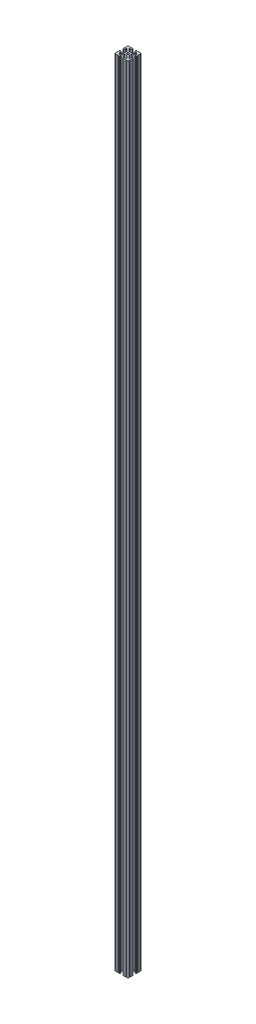
SolidWorks part; units mm, degrees
ref_plane "Piano frontale" through (0, 0, 0) normal (0, 0, 1) x (1, 0, 0)
ref_plane "Piano superiore" through (0, 0, 0) normal (0, 1, 0) x (1, 0, 0)
ref_plane "Piano destro" through (0, 0, 0) normal (1, 0, 0) x (0, 0, -1)
ref_plane "Piano1" through (0, 152.4, 0) normal (0, 1, 0) x (1, 0, 0)
sketch "Schizzo1" plane through (0, 152.4, 0) normal (0, 1, 0) x (1, 0, 0)
  line L0 (130, 32) -> (130, 33.688)
  line L1 (130, 34.312) -> (130, 37.688)
  line L2 (130, 38.312) -> (130, 40.4)
  line L3 (128.6, 41.8) -> (128.2, 41.8)
  line L4 (126.8, 40.4) -> (126.8, 37.3941)
  line L5 (125.4343, 36.8284) -> (120.9058, 41.357)
  line L6 (120.32, 42.7712) -> (120.32, 47.2288)
  line L7 (120.9058, 48.643) -> (125.4343, 53.1716)
  line L8 (126.8, 52.6059) -> (126.8, 49.6)
  line L9 (128.2, 48.2) -> (128.6, 48.2)
  line L10 (130, 49.6) -> (130, 51.688)
  line L11 (130, 52.312) -> (130, 55.688)
  line L12 (130, 56.312) -> (130, 58)
  line L13 (128, 60) -> (126.312, 60)
  line L14 (125.688, 60) -> (122.312, 60)
  line L15 (121.688, 60) -> (119.6, 60)
  line L16 (118.2, 58.6) -> (118.2, 58.2)
  line L17 (119.6, 56.8) -> (122.6059, 56.8)
  line L18 (123.1716, 55.4343) -> (118.643, 50.9058)
  line L19 (117.2288, 50.32) -> (112.7712, 50.32)
  line L20 (111.357, 50.9058) -> (106.8284, 55.4343)
  line L21 (107.3941, 56.8) -> (110.4, 56.8)
  line L22 (111.8, 58.2) -> (111.8, 58.6)
  line L23 (110.4, 60) -> (108.312, 60)
  line L24 (107.688, 60) -> (104.312, 60)
  line L25 (103.688, 60) -> (102, 60)
  line L26 (100, 58) -> (100, 56.312)
  line L27 (100, 55.688) -> (100, 52.312)
  line L28 (100, 51.688) -> (100, 49.6)
  line L29 (101.4, 48.2) -> (101.8, 48.2)
  line L30 (103.2, 49.6) -> (103.2, 52.6059)
  line L31 (104.5657, 53.1716) -> (109.0942, 48.643)
  line L32 (109.68, 47.2288) -> (109.68, 42.7712)
  line L33 (109.0942, 41.357) -> (104.5657, 36.8284)
  line L34 (103.2, 37.3941) -> (103.2, 40.4)
  line L35 (101.8, 41.8) -> (101.4, 41.8)
  line L36 (100, 40.4) -> (100, 38.312)
  line L37 (100, 37.688) -> (100, 34.312)
  line L38 (100, 33.688) -> (100, 32)
  line L39 (102, 30) -> (103.688, 30)
  line L40 (104.312, 30) -> (107.688, 30)
  line L41 (108.312, 30) -> (110.4, 30)
  line L42 (111.8, 31.4) -> (111.8, 31.8)
  line L43 (110.4, 33.2) -> (107.3941, 33.2)
  line L44 (106.8284, 34.5657) -> (111.357, 39.0942)
  line L45 (112.7712, 39.68) -> (117.2288, 39.68)
  line L46 (118.643, 39.0942) -> (123.1716, 34.5657)
  line L47 (122.6059, 33.2) -> (119.6, 33.2)
  line L48 (118.2, 31.8) -> (118.2, 31.4)
  line L49 (119.6, 30) -> (121.688, 30)
  line L50 (122.312, 30) -> (125.688, 30)
  line L51 (126.312, 30) -> (128, 30)
  circle A0 centre (115, 45) radius 2.62
  arc A1 (128, 30) -> (130, 32) centre (128, 32) ccw
  arc A2 (130, 33.688) -> (130, 34.312) centre (130, 34) cw
  arc A3 (130, 37.688) -> (130, 38.312) centre (130, 38) cw
  arc A4 (130, 40.4) -> (128.6, 41.8) centre (128.6, 40.4) ccw
  arc A5 (128.2, 41.8) -> (126.8, 40.4) centre (128.2, 40.4) ccw
  arc A6 (126.8, 37.3941) -> (125.4343, 36.8284) centre (126, 37.3941) cw
  arc A7 (120.9058, 41.357) -> (120.32, 42.7712) centre (122.32, 42.7712) cw
  arc A8 (120.32, 47.2288) -> (120.9058, 48.643) centre (122.32, 47.2288) cw
  arc A9 (125.4343, 53.1716) -> (126.8, 52.6059) centre (126, 52.6059) cw
  arc A10 (126.8, 49.6) -> (128.2, 48.2) centre (128.2, 49.6) ccw
  arc A11 (128.6, 48.2) -> (130, 49.6) centre (128.6, 49.6) ccw
  arc A12 (130, 51.688) -> (130, 52.312) centre (130, 52) cw
  arc A13 (130, 55.688) -> (130, 56.312) centre (130, 56) cw
  arc A14 (130, 58) -> (128, 60) centre (128, 58) ccw
  arc A15 (126.312, 60) -> (125.688, 60) centre (126, 60) cw
  arc A16 (122.312, 60) -> (121.688, 60) centre (122, 60) cw
  arc A17 (119.6, 60) -> (118.2, 58.6) centre (119.6, 58.6) ccw
  arc A18 (118.2, 58.2) -> (119.6, 56.8) centre (119.6, 58.2) ccw
  arc A19 (122.6059, 56.8) -> (123.1716, 55.4343) centre (122.6059, 56) cw
  arc A20 (118.643, 50.9058) -> (117.2288, 50.32) centre (117.2288, 52.32) cw
  arc A21 (112.7712, 50.32) -> (111.357, 50.9058) centre (112.7712, 52.32) cw
  arc A22 (106.8284, 55.4343) -> (107.3941, 56.8) centre (107.3941, 56) cw
  arc A23 (110.4, 56.8) -> (111.8, 58.2) centre (110.4, 58.2) ccw
  arc A24 (111.8, 58.6) -> (110.4, 60) centre (110.4, 58.6) ccw
  arc A25 (108.312, 60) -> (107.688, 60) centre (108, 60) cw
  arc A26 (104.312, 60) -> (103.688, 60) centre (104, 60) cw
  arc A27 (102, 60) -> (100, 58) centre (102, 58) ccw
  arc A28 (100, 56.312) -> (100, 55.688) centre (100, 56) cw
  arc A29 (100, 52.312) -> (100, 51.688) centre (100, 52) cw
  arc A30 (100, 49.6) -> (101.4, 48.2) centre (101.4, 49.6) ccw
  arc A31 (101.8, 48.2) -> (103.2, 49.6) centre (101.8, 49.6) ccw
  arc A32 (103.2, 52.6059) -> (104.5657, 53.1716) centre (104, 52.6059) cw
  arc A33 (109.0942, 48.643) -> (109.68, 47.2288) centre (107.68, 47.2288) cw
  arc A34 (109.68, 42.7712) -> (109.0942, 41.357) centre (107.68, 42.7712) cw
  arc A35 (104.5657, 36.8284) -> (103.2, 37.3941) centre (104, 37.3941) cw
  arc A36 (103.2, 40.4) -> (101.8, 41.8) centre (101.8, 40.4) ccw
  arc A37 (101.4, 41.8) -> (100, 40.4) centre (101.4, 40.4) ccw
  arc A38 (100, 38.312) -> (100, 37.688) centre (100, 38) cw
  arc A39 (100, 34.312) -> (100, 33.688) centre (100, 34) cw
  arc A40 (100, 32) -> (102, 30) centre (102, 32) ccw
  arc A41 (103.688, 30) -> (104.312, 30) centre (104, 30) cw
  arc A42 (107.688, 30) -> (108.312, 30) centre (108, 30) cw
  arc A43 (110.4, 30) -> (111.8, 31.4) centre (110.4, 31.4) ccw
  arc A44 (111.8, 31.8) -> (110.4, 33.2) centre (110.4, 31.8) ccw
  arc A45 (107.3941, 33.2) -> (106.8284, 34.5657) centre (107.3941, 34) cw
  arc A46 (111.357, 39.0942) -> (112.7712, 39.68) centre (112.7712, 37.68) cw
  arc A47 (117.2288, 39.68) -> (118.643, 39.0942) centre (117.2288, 37.68) cw
  arc A48 (123.1716, 34.5657) -> (122.6059, 33.2) centre (122.6059, 34) cw
  arc A49 (119.6, 33.2) -> (118.2, 31.8) centre (119.6, 31.8) ccw
  arc A50 (118.2, 31.4) -> (119.6, 30) centre (119.6, 31.4) ccw
  arc A51 (121.688, 30) -> (122.312, 30) centre (122, 30) cw
  arc A52 (125.688, 30) -> (126.312, 30) centre (126, 30) cw
  dimension "D1" = 30
  dimension "D2" = 30
extrude "Estrusione-Estrusione1" add sketch "Schizzo1" against normal blind 1780
